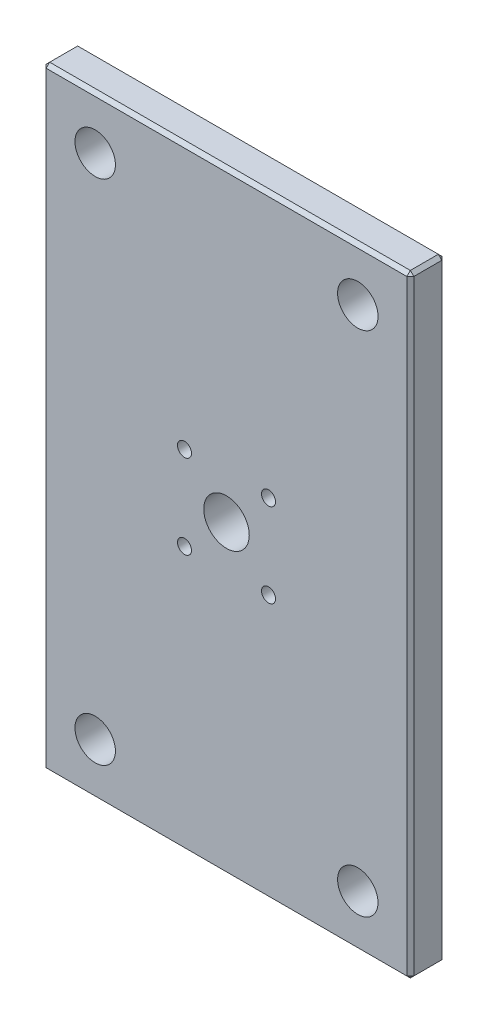
SolidWorks part; units mm, degrees
ref_plane "前视基准面" through (0, 0, 0) normal (0, 0, 1) x (1, 0, 0)
ref_plane "上视基准面" through (0, 0, 0) normal (0, 1, 0) x (1, 0, 0)
ref_plane "右视基准面" through (0, 0, 0) normal (1, 0, 0) x (0, 0, -1)
sketch "草图1" plane through (0, 0, 0) normal (0, 0, 1) x (1, 0, 0)
  line L1 (0, 0) -> (420, 0)
  line L2 (0, 0) -> (0, 700)
  line L3 (0, 700) -> (420, 700)
  line L4 (420, 0) -> (420, 700)
  dimension "D1" = 700
  dimension "D2" = 420
extrude "凸台-拉伸1" add sketch "草图1" along normal blind 40
sketch "草图2" plane through (0, 0, 40) normal (0, 0, 1) x (1, 0, 0)
  line L0 (0, 700) -> (0, 0) construction
  line L1 (420, 700) -> (0, 700) construction
  line L2 (420, 0) -> (420, 700) construction
  line L3 (0, 0) -> (420, 0) construction
  circle A0 centre (60, 60) radius 23.1
  circle A1 centre (360, 60) radius 23.1
  circle A2 centre (360, 640) radius 23.1
  circle A3 centre (60, 640) radius 23.1
  dimension "D1" = 46.2
  dimension "D2" = 46.2
  dimension "D3" = 46.2
  dimension "D4" = 46.2
  dimension "D5" = 60
  dimension "D6" = 60
  dimension "D7" = 60
  dimension "D8" = 60
  dimension "D9" = 60
  dimension "D10" = 60
  dimension "D11" = 60
  dimension "D12" = 60
extrude "切除-拉伸1" cut sketch "草图2" against normal through all
sketch "草图3" plane through (0, 0, 40) normal (0, 0, 1) x (1, 0, 0)
  line L0 (0, 700) -> (0, 0) construction
  line L1 (0, 0) -> (420, 0) construction
  circle A0 centre (210, 350) radius 26
  dimension "D1" = 52
  dimension "D2" = 210
  dimension "D3" = 350
extrude "切除-拉伸2" cut sketch "草图3" against normal through all
hole_wizard "M18x2.0 螺纹孔1" positions "草图5" profile "草图4" tap size "M18x2.0" standard "Ansi Metric" end condition through all
sketch "草图5" plane through (0, 0, 40) normal (0, 0, 1) x (1, 0, 0)
  circle A0 centre (210, 350) radius 26 construction
  point P0 (162, 398)
  point P2 (258, 398)
  point P4 (258, 302)
  point P6 (162, 302)
  dimension "D5" = 48
  dimension "D8" = 48
  dimension "D1" = 96
  dimension "D2" = 96
  dimension "D3" = 96
  dimension "D4" = 96
  dimension "D6" = 48
  dimension "D7" = 48
cosmetic thread "孔螺蚊线1" parameters "D2"=18
cosmetic thread "孔螺蚊线2" parameters "D2"=18
cosmetic thread "孔螺蚊线3" parameters "D2"=18
cosmetic thread "孔螺蚊线4" parameters "D2"=18
sketch "草图4" plane through (162, 398, 40) normal (1, 0, 0) x (0, -1, 0)
  line L0 (0, 0) -> (0, 40)
  line L1 (0, 40) -> (8, 40)
  line L2 (8, 40) -> (8, 0)
  line L5 (8, 0) -> (0, 0)
  line L11 (0, -6.35) -> (0, 107.95) construction
  dimension "通孔螺纹孔钻头直径" = 16
  dimension "通孔螺纹孔钻头深度" = 40
chamfer "倒角1" distance 4 angle 45 12 edges at (210, 0, 40) (210, 0, 0) (0, 350, 40) (0, 0, 20) (0, 350, 0) (210, 700, 40) (0, 700, 20) (210, 700, 0) (420, 0, 20) (420, 350, 40) (420, 700, 20) (420, 350, 0)
hole_wizard "M4 螺纹孔1" positions "草图7" profile "草图6" tap size "M4" standard "Gb"
sketch "草图7" plane through (0, 0, 0) normal (0, -1, 0) x (-1, 0, 0)
  line L0 (-210, 44.2494) -> (-210, -121.2875) construction
  point P0 (-237, -20)
  point P3 (-183, -20)
  dimension "D1" = 54
  dimension "D2" = 27
sketch "草图6" plane through (237, 0, 20) normal (1, 0, 0) x (0, 0, -1)
  line L0 (0, 0) -> (0, 11.0914)
  line L1 (0, 11.0914) -> (1.65, 10.1)
  line L2 (1.65, 10.1) -> (1.65, 0)
  line L5 (1.65, 0) -> (0, 0)
  line L10 (0, 11.0914) -> (-1.65, 10.1) construction
  line L11 (0, -6.35) -> (0, 107.95) construction
  dimension "螺纹孔钻头直径" = 3.3
  dimension "螺纹孔钻头深度" = 10.1
  dimension "导头角度" = 118
cosmetic thread "孔螺蚊线5" parameters "D1"=8, "D2"=4
cosmetic thread "孔螺蚊线6" parameters "D1"=8, "D2"=4
